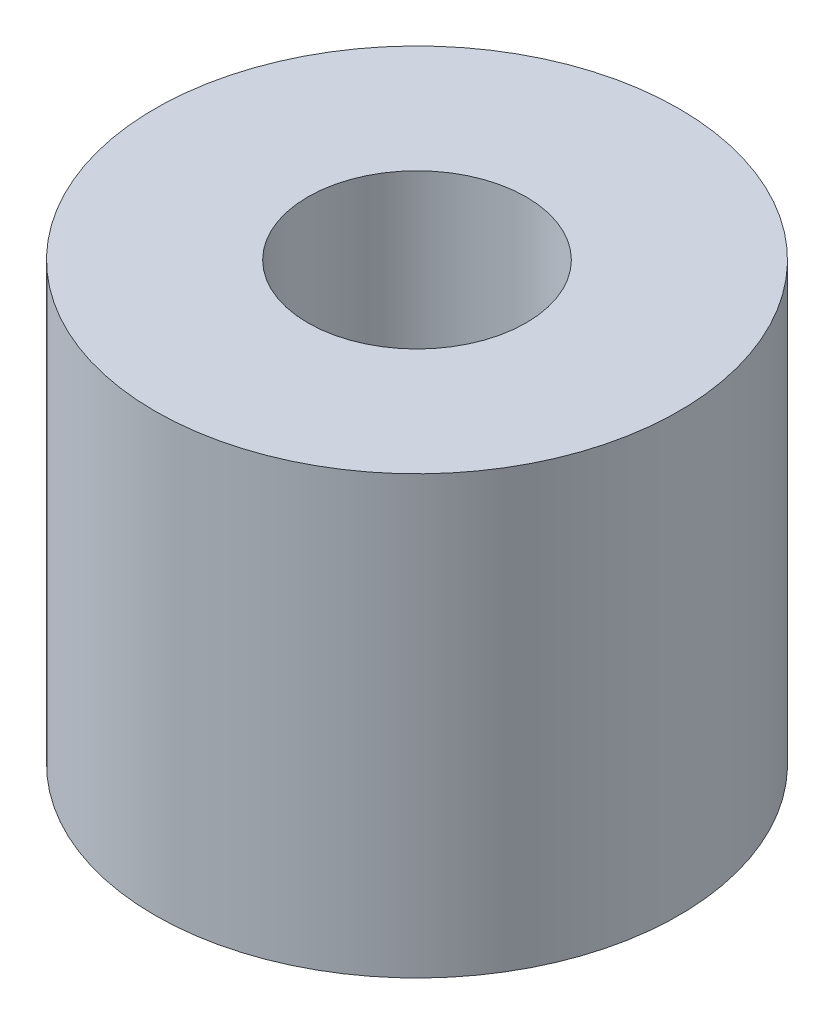
SolidWorks part; units mm, degrees
ref_plane "Front" through (0, 0, 0) normal (0, 0, 1) x (1, 0, 0)
ref_plane "Top" through (0, 0, 0) normal (0, 1, 0) x (1, 0, 0)
ref_plane "Right" through (0, 0, 0) normal (1, 0, 0) x (0, 0, -1)
sketch "Croquis1" plane through (0, 0, 0) normal (0, 1, 0) x (1, 0, 0)
  circle A0 centre (0, 0) radius 25
  dimension "D1" = 50
extrude "Saliente-Extruir1" add sketch "Croquis1" along normal blind 10
sketch "Croquis2" plane through (0, 10, 0) normal (0, 1, 0) x (1, 0, 0)
  circle A0 centre (0, 0) radius 60
  dimension "D1" = 120
extrude "Saliente-Extruir2" add sketch "Croquis2" along normal blind 100
sketch "Croquis3" plane through (0, 110, 0) normal (0, 1, 0) x (1, 0, 0)
  circle A0 centre (0, 0) radius 25
  dimension "D1" = 50
extrude "Cortar-Extruir1" cut sketch "Croquis3" against normal blind 50
